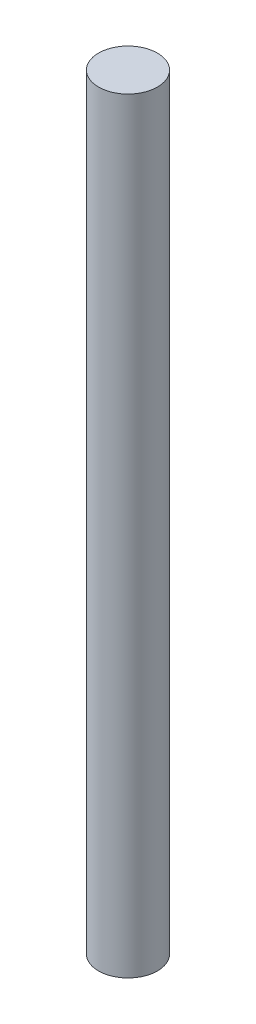
SolidWorks part; units mm, degrees
ref_plane "Front Plane" through (0, 0, 0) normal (0, 0, 1) x (1, 0, 0)
ref_plane "Top Plane" through (0, 0, 0) normal (0, 1, 0) x (1, 0, 0)
ref_plane "Right Plane" through (0, 0, 0) normal (1, 0, 0) x (0, 0, -1)
sketch "Sketch1" plane through (0, 0, 0) normal (0, 1, 0) x (1, 0, 0)
  circle A0 centre (0, 0) radius 3.175
  dimension "D1" = 6.35
extrude "Boss-Extrude1" add sketch "Sketch1" along normal blind 82.55
